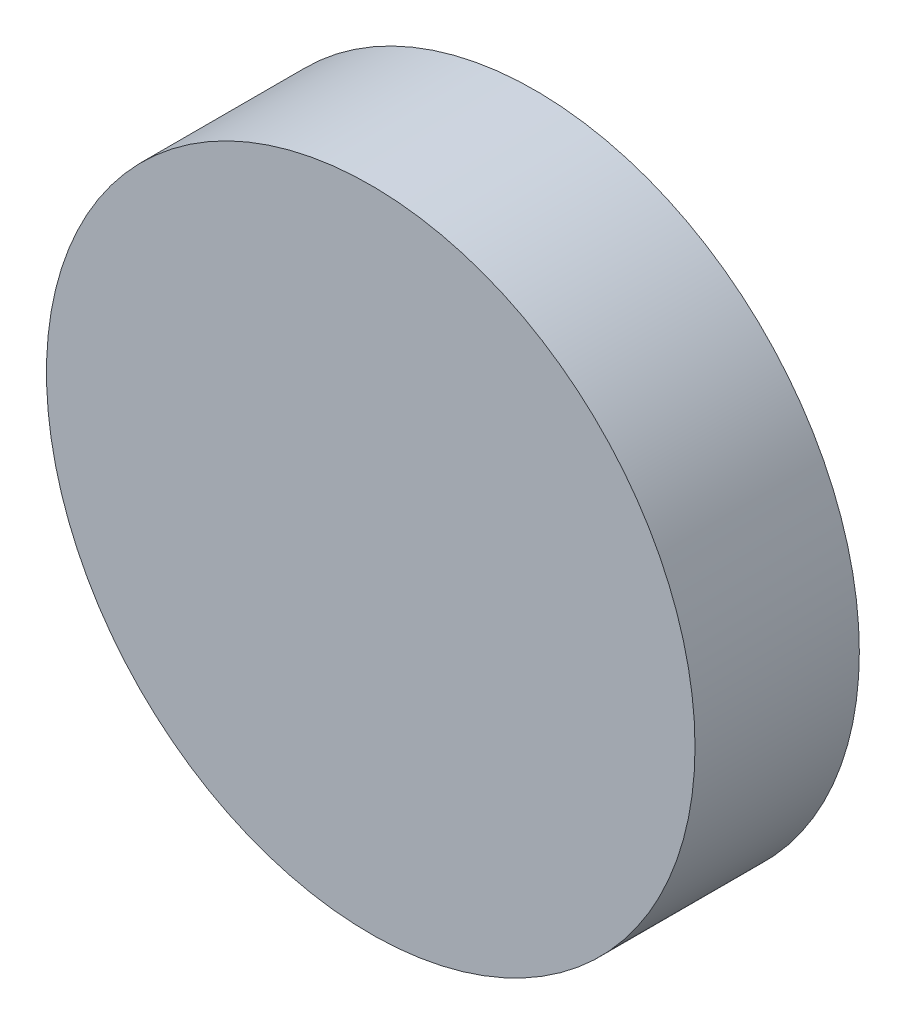
SolidWorks part; units mm, degrees
ref_plane "Front Plane" through (0, 0, 0) normal (0, 0, 1) x (1, 0, 0)
ref_plane "Top Plane" through (0, 0, 0) normal (0, 1, 0) x (1, 0, 0)
ref_plane "Right Plane" through (0, 0, 0) normal (1, 0, 0) x (0, 0, -1)
sketch "Sketch1" plane through (0, 0, 0) normal (0, 0, 1) x (1, 0, 0)
  circle A0 centre (-47.0348, 0) radius 19.7332
extrude "Boss-Extrude1" add sketch "Sketch1" along normal blind 10
